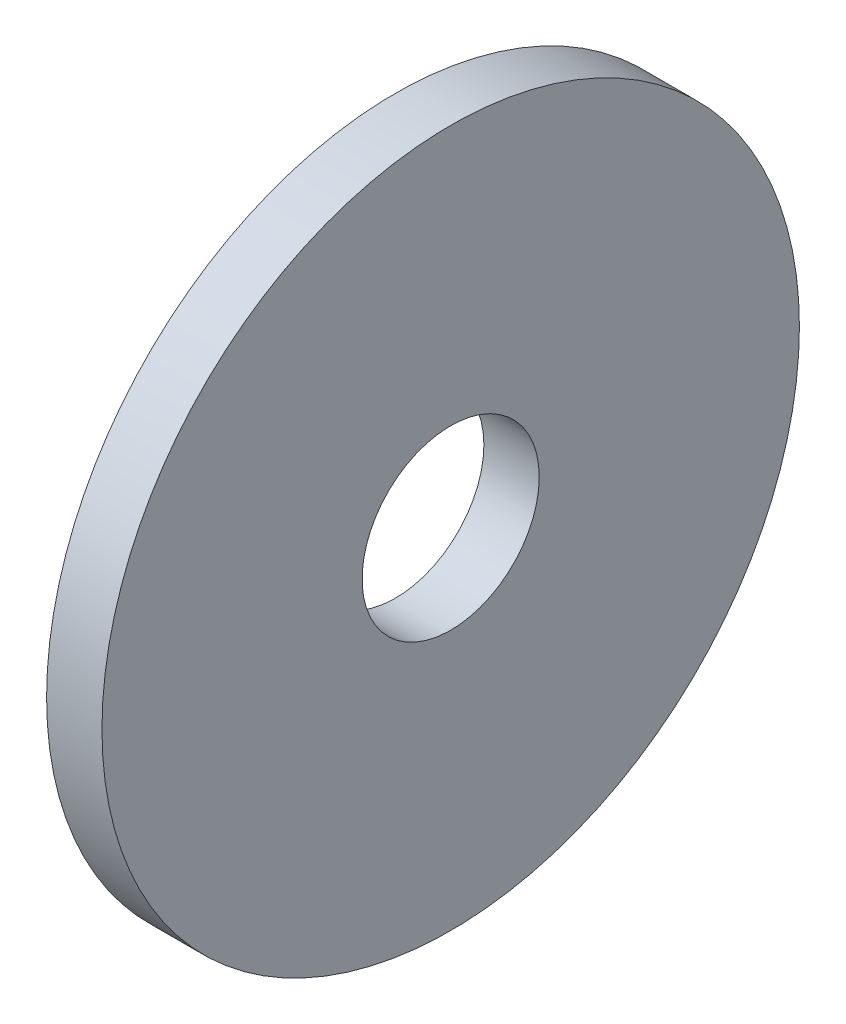
SolidWorks part; units mm, degrees
ref_plane "正面" through (0, 0, 0) normal (0, 0, 1) x (1, 0, 0)
ref_plane "平面" through (0, 0, 0) normal (0, 1, 0) x (1, 0, 0)
ref_plane "右側面" through (0, 0, 0) normal (1, 0, 0) x (0, 0, -1)
sketch "ｽｹｯﾁ1" plane through (0, 0, 0) normal (1, 0, 0) x (0, 0, -1)
  circle A0 centre (0, 0) radius 15.75
  circle A1 centre (0, 0) radius 4
  dimension "D1" = 31.5
  dimension "D2" = 8
extrude "ﾎﾞｽ - 押し出し1" add sketch "ｽｹｯﾁ1" along normal blind 2.5
